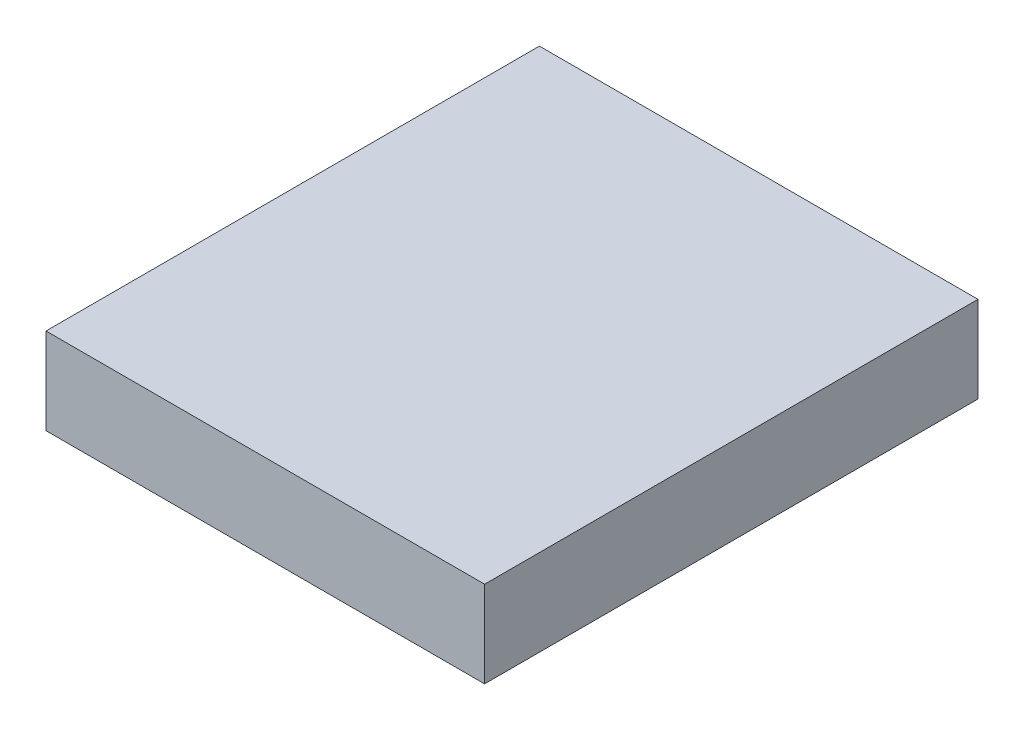
SolidWorks part; units mm, degrees
ref_plane "Front Plane" through (0, 0, 0) normal (0, 0, 1) x (1, 0, 0)
ref_plane "Top Plane" through (0, 0, 0) normal (0, 1, 0) x (1, 0, 0)
ref_plane "Right Plane" through (0, 0, 0) normal (1, 0, 0) x (0, 0, -1)
sketch "Sketch1" plane through (0, 0, 0) normal (0, 1, 0) x (1, 0, 0)
  line L1 (-50.8, -57.15) -> (50.8, -57.15)
  line L2 (-50.8, -57.15) -> (-50.8, 57.15)
  line L3 (-50.8, 57.15) -> (50.8, 57.15)
  line L4 (50.8, -57.15) -> (50.8, 57.15)
  line L5 (-50.8, -57.15) -> (50.8, 57.15) construction
  line L6 (-50.8, 57.15) -> (50.8, -57.15) construction
  point P0 (0, 0)
  dimension "D1" = 101.6
  dimension "D2" = 114.3
extrude "Boss-Extrude1" add sketch "Sketch1" along normal blind 20
